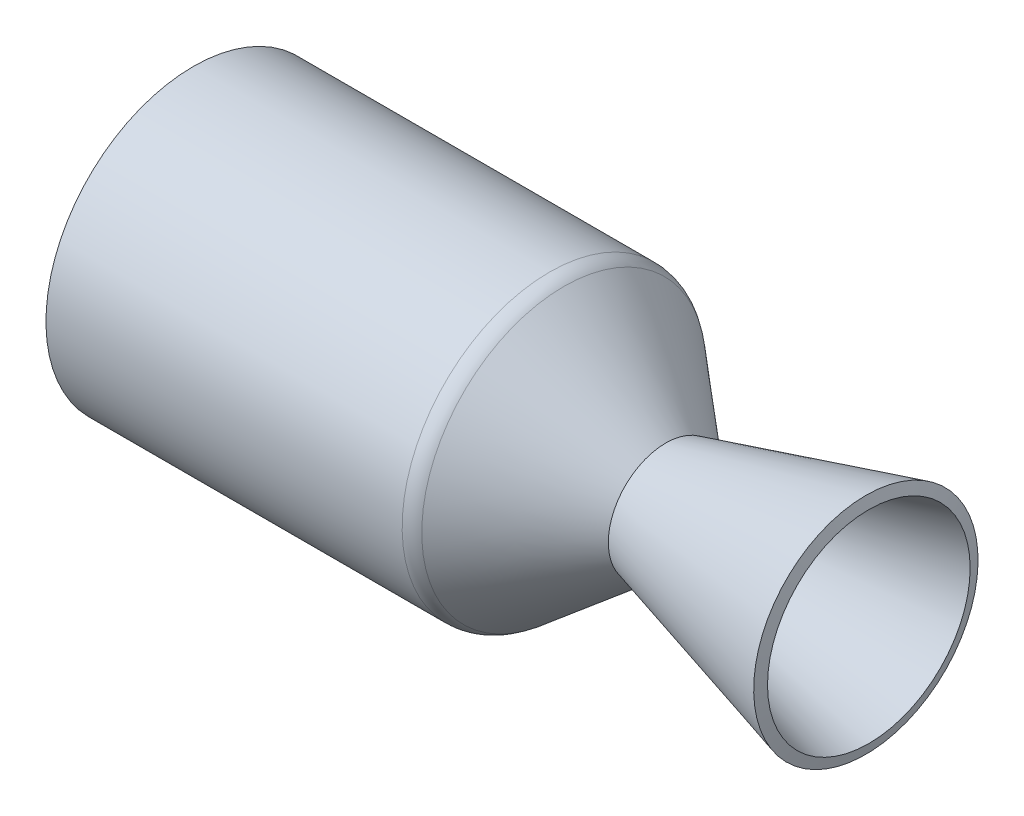
SolidWorks part; units mm, degrees
ref_plane "Front Plane" through (0, 0, 0) normal (0, 0, 1) x (1, 0, 0)
ref_plane "Top Plane" through (0, 0, 0) normal (0, 1, 0) x (1, 0, 0)
ref_plane "Right Plane" through (0, 0, 0) normal (1, 0, 0) x (0, 0, -1)
sketch "Sketch4" plane through (0, 0, 0) normal (0, 0, 1) x (1, 0, 0)
  line L0 (196.9247, 0) -> (-103.0753, 0) construction
  line L1 (-103.0753, 65.4514) -> (55.1165, 65.4514)
  line L2 (-103.0753, 60.4514) -> (55.1165, 60.4514)
  line L3 (58.3147, 59.2948) -> (103.5318, 21.6672)
  line L4 (61.513, 63.1381) -> (106.73, 25.5105)
  line L5 (196.9247, 45) -> (108.0493, 20.6877)
  line L6 (195.6055, 49.8228) -> (106.73, 25.5105)
  line L7 (-103.0753, 65.4514) -> (-103.0753, 60.4514)
  line L8 (195.6055, 49.8228) -> (196.9247, 45)
  arc A0 (103.5318, 21.6672) -> (108.0493, 20.6877) centre (106.73, 25.5105) ccw
  arc A1 (55.1165, 60.4514) -> (58.3147, 59.2948) centre (55.1165, 55.4514) cw
  arc A2 (55.1165, 65.4514) -> (61.513, 63.1381) centre (55.1165, 55.4514) cw
  arc A3 (106.73, 25.5105) -> (106.73, 25.5105) centre (106.73, 25.5105) ccw
  point P13 (56.9247, 60.4514)
  dimension "D5" = 5
  dimension "D1" = 160
  dimension "D2" = 300
  dimension "D3" = 45
  dimension "D4" = 60.4514
  dimension "D6" = 5
revolve "Revolve3" add sketch "Sketch4" angle 360 about L0
